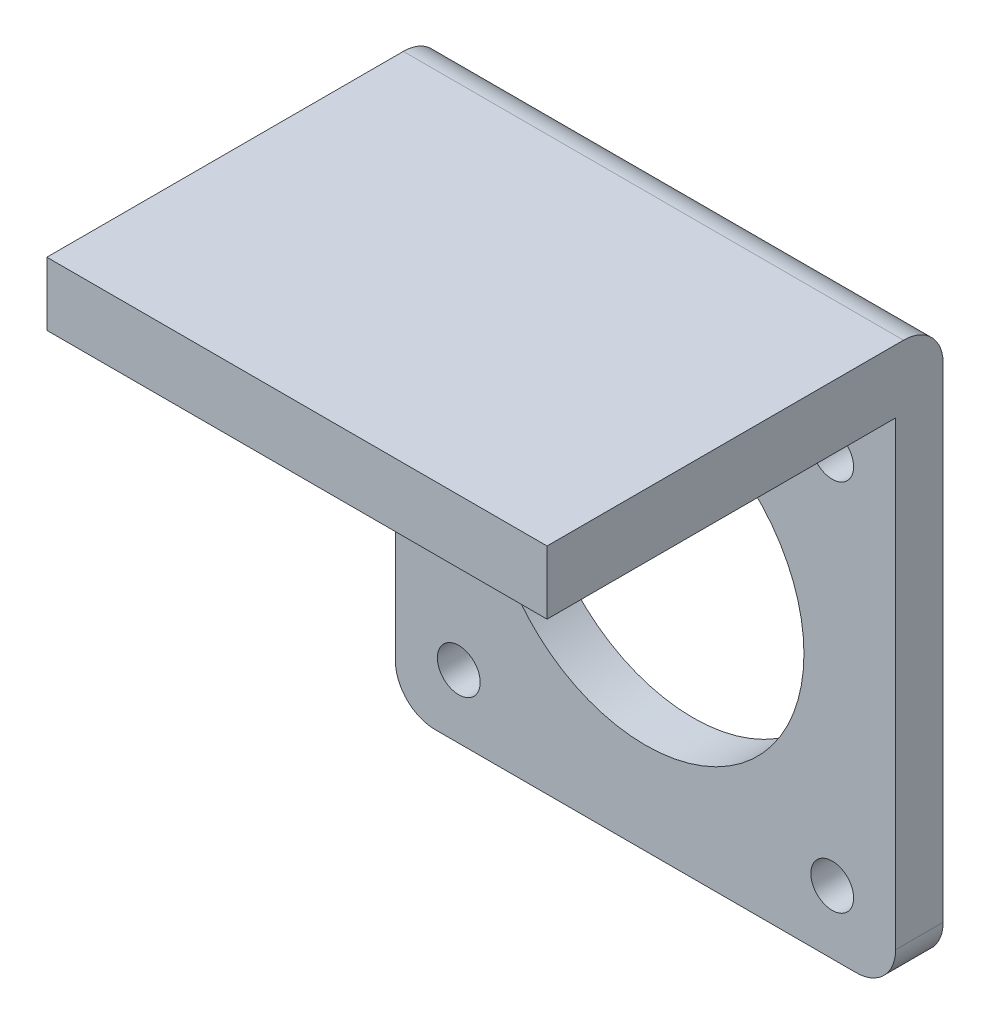
SolidWorks part; units mm, degrees
ref_plane "Alzado" through (0, 0, 0) normal (0, 0, 1) x (1, 0, 0)
ref_plane "Planta" through (0, 0, 0) normal (0, 1, 0) x (1, 0, 0)
ref_plane "Vista lateral" through (0, 0, 0) normal (1, 0, 0) x (0, 0, -1)
sketch "Croquis1" plane through (0, 0, 0) normal (0, 0, 1) x (1, 0, 0)
  line L0 (0, 0) -> (47.14, -47.14) construction
  line L2 (0, -47.14) -> (47.14, -47.14)
  line L3 (0, -47.14) -> (0, 0)
  line L4 (0, 0) -> (47.14, 0)
  line L5 (47.14, -47.14) -> (47.14, 0)
  line L9 (-8, -50.14) -> (-8, 8)
  line L10 (-8, 8) -> (55.14, 8)
  line L11 (55.14, -50.14) -> (55.14, 8)
  line L12 (-3, -55.14) -> (50.14, -55.14)
  line L13 (55.14, -55.14) -> (55.14, 8) construction
  line L14 (-8, -55.14) -> (55.14, -55.14) construction
  line L15 (-8, -55.14) -> (-8, 8) construction
  circle A0 centre (0, 0) radius 2.7
  circle A1 centre (47.14, 0) radius 2.7
  circle A2 centre (47.14, -47.14) radius 2.7
  circle A3 centre (0, -47.14) radius 2.7
  circle A4 centre (23.57, -23.57) radius 20
  arc A5 (55.14, -50.14) -> (50.14, -55.14) centre (50.14, -50.14) cw
  arc A6 (-8, -50.14) -> (-3, -55.14) centre (-3, -50.14) ccw
  dimension "D1" = 5.4
  dimension "D4" = 40
  dimension "D6" = 5
  dimension "D7" = 47.14
  dimension "D5" = 8
  dimension "D2" = 2
  dimension "D3" = 2
extrude "Saliente-Extruir1" add sketch "Croquis1" along normal blind 6
sketch "Croquis2" plane through (0, 0, 0) normal (0, 0, -1) x (-1, 0, 0)
  line L1 (-55.14, 8) -> (8, 8)
  line L2 (-55.14, 8) -> (-55.14, 16)
  line L3 (-55.14, 16) -> (8, 16)
  line L4 (8, 8) -> (8, 16)
  dimension "D1" = 8
extrude "Saliente-Extruir2" add sketch "Croquis2" against normal blind 50
fillet "Redondeo1" radius 5 1 edges at (23.57, 16, 0)
